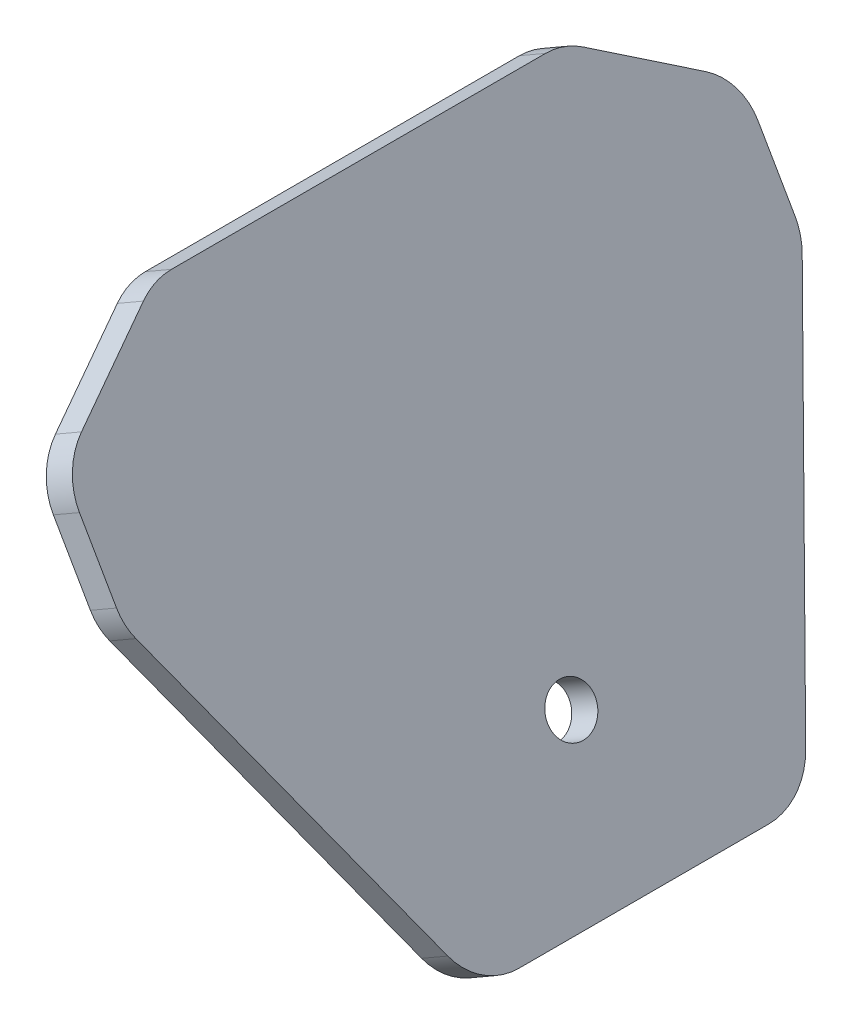
SolidWorks part; units mm, degrees
material "Teak"
ref_plane "Front Plane" through (0, 0, 0) normal (0, 0, 1) x (1, 0, 0)
ref_plane "Top Plane" through (0, 0, 0) normal (0, 1, 0) x (1, 0, 0)
ref_plane "Right Plane" through (0, 0, 0) normal (1, 0, 0) x (0, 0, -1)
sketch "Sketch1" plane through (460.697, 265.9835, 0) normal (0.866, 0.5, 0) x (0, 0, -1)
  line L1 (-748.2099, 226.0456) -> (-705.0299, 226.0456)
  line L2 (-705.0299, 226.0456) -> (-690.8865, 216.7807)
  line L3 (-690.8865, 216.7807) -> (-690.8865, 204.0807)
  line L4 (-509.2464, 204.0807) -> (-1195.0464, 204.0807) construction
  line L5 (-748.2099, 226.0456) -> (-762.3532, 216.7807)
  line L6 (-762.3532, 216.7807) -> (-762.3532, 204.0807)
  line L7 (-739.4339, 234.5374) -> (-710.8589, 234.5374) construction
  line L8 (-739.4339, 229.1689) -> (-739.4339, 309.2945) construction
  line L9 (-710.8589, 229.8837) -> (-710.8589, 308.5797) construction
  line L10 (-710.8589, 234.5374) -> (-725.1464, 234.5374) construction
  line L11 (-725.1464, 234.5374) -> (-725.1464, 207.0988) construction
  line L13 (-762.3532, 204.0807) -> (-743.7255, 165.9807)
  line L14 (-690.8865, 204.0807) -> (-709.5142, 165.9807)
  line L15 (-709.5142, 165.9807) -> (-743.7255, 165.9807)
  dimension "D1" = 38.1
extrude "Boss-Extrude1" add sketch "Sketch1" along normal blind 3.175
fillet "Fillet1" radius 6.35
sketch "Sketch2" plane through (463.4466, 267.571, 0) normal (0.866, 0.5, 0) x (0, 0, -1)
  line L0 (-726.6199, 165.9807) -> (-726.6199, 211.8258) construction
  line L1 (-739.7618, 165.9807) -> (-713.4779, 165.9807) construction
  circle A0 centre (-726.6199, 181.2207) radius 2.5
  dimension "D1" = 15.24
extrude "Cut-Extrude1" cut sketch "Sketch2" against normal blind 12.192
sketch "Sketch3" plane through (463.4466, 267.571, 0) normal (0.866, 0.5, 0) x (0, 0, -1)
  line L0 (-690.8865, 205.5499) -> (-762.3532, 205.5499) construction
  line L1 (-726.6199, 226.0456) -> (-726.6199, 165.9807) construction
  line L2 (-706.9245, 226.0456) -> (-746.3152, 226.0456) construction
  line L3 (-739.7618, 165.9807) -> (-713.4779, 165.9807) construction
  arc A0 (-691.5318, 202.7608) -> (-690.8865, 205.5499) centre (-697.2365, 205.5499) ccw construction
  point P12 (-726.6199, 205.5499)
